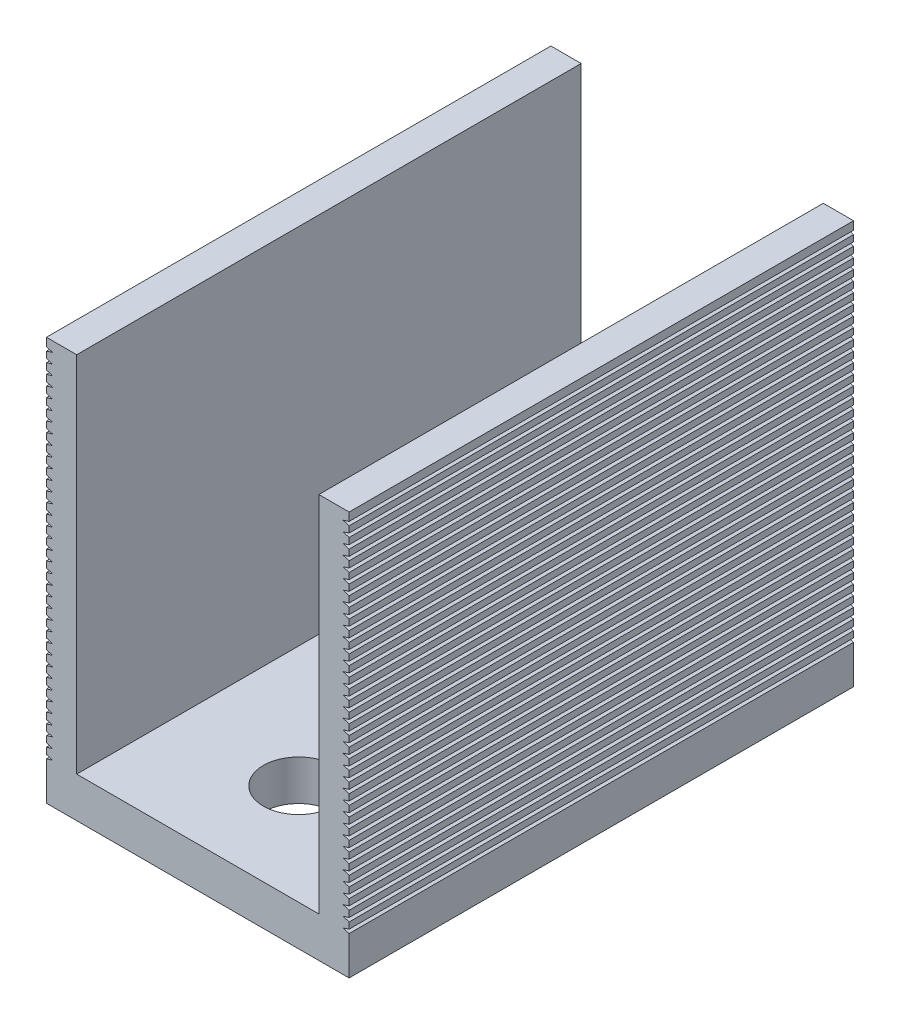
SolidWorks part; units mm, degrees
ref_plane "Front Plane" through (0, 0, 0) normal (0, 0, 1) x (1, 0, 0)
ref_plane "Top Plane" through (0, 0, 0) normal (0, 1, 0) x (1, 0, 0)
ref_plane "Right Plane" through (0, 0, 0) normal (1, 0, 0) x (0, 0, -1)
sketch "Sketch1" plane through (0, 0, 0) normal (0, 0, 1) x (1, 0, 0)
  line L0 (-12.6275, 0) -> (15.917, 0) construction
  line L1 (0, 14.6819) -> (0, -8.6749) construction
  line L2 (-7.5, 20) -> (-7.5, 0)
  line L3 (-7.5, 0) -> (7.5, 0)
  line L4 (7.5, 0) -> (7.5, 20)
  line L5 (7.5, 20) -> (6, 20)
  line L6 (6, 20) -> (6, 2)
  line L7 (6, 2) -> (-6, 2)
  line L8 (-6, 2) -> (-6, 20)
  line L9 (-6, 20) -> (-7.5, 20)
  dimension "D1" = 15
  dimension "D2" = 12
  dimension "D3" = 20
  dimension "D4" = 2
extrude "Boss-Extrude1" add sketch "Sketch1" along normal blind 25
sketch "Sketch2" plane through (0, 2, 0) normal (0, 1, 0) x (1, 0, 0)
  line L0 (6, -25) -> (-6, -25) construction
  line L1 (0, 4.599) -> (0, -28.6976) construction
  line L2 (6, -25) -> (6, 0) construction
  line L3 (-6, 8.8523) -> (6, 8.8523)
  line L4 (-6, 8.8523) -> (-6, -6)
  line L5 (-6, -6) -> (6, -6)
  line L6 (6, 8.8523) -> (6, -6)
  line L7 (-6, 8.8523) -> (6, -6) construction
  line L8 (-6, -6) -> (6, 8.8523) construction
  circle A0 centre (0, -20) radius 1.75
  point P7 (0, 1.4261)
  dimension "D2" = 3.5
  dimension "D1" = 5
  dimension "D3" = 19
extrude "Cut-Extrude1" cut sketch "Sketch2" against normal blind 25
sketch "Sketch3" plane through (0, 0, 25) normal (0, 0, 1) x (1, 0, 0)
  line L0 (-8, 19.75) -> (-7.2, 19.5)
  line L1 (-7.2, 19.5) -> (-8, 19.25)
  line L2 (-8, 19.25) -> (-8, 19.75)
  line L3 (-7.5, 20) -> (-7.5, 0) construction
  line L4 (-9.6157, 19.5) -> (-5.3447, 19.5) construction
  line L5 (-6, 20) -> (-7.5, 20) construction
  dimension "D1" = 0.3
  dimension "D2" = 0.5
  dimension "D3" = 0.5
  dimension "D4" = 0.5
extrude "Cut-Extrude2" cut sketch "Sketch3" against normal through all
pattern_linear "LPattern1" count 36 spacing 0.5 along (0, -1, 0) of "Cut-Extrude2"
mirror "Mirror1" about plane through (0, 0, 0) normal (1, 0, 0) of "LPattern1", "Cut-Extrude2"
